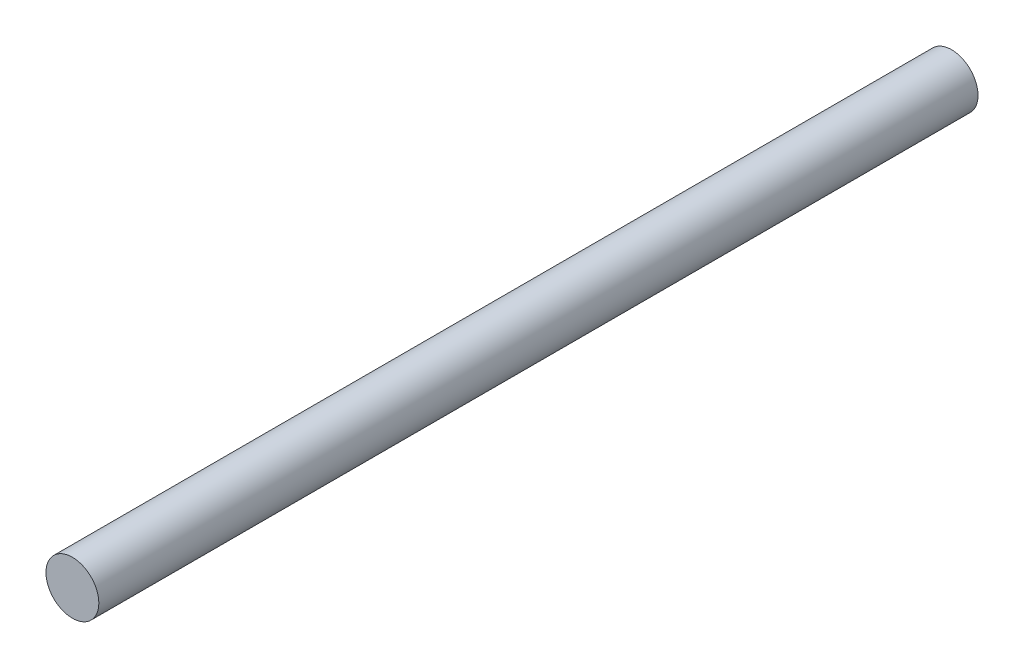
SolidWorks part; units mm, degrees
material "6061 Alloy"
ref_plane "Front Plane" through (0, 0, 0) normal (0, 0, 1) x (1, 0, 0)
ref_plane "Top Plane" through (0, 0, 0) normal (0, 1, 0) x (1, 0, 0)
ref_plane "Right Plane" through (0, 0, 0) normal (1, 0, 0) x (0, 0, -1)
sketch "Sketch1" plane through (0, 0, 0) normal (0, 0, 1) x (1, 0, 0)
  circle A0 centre (0, 0) radius 3
  dimension "D1" = 6
extrude "Boss-Extrude1" add sketch "Sketch1" along normal blind 99.765
